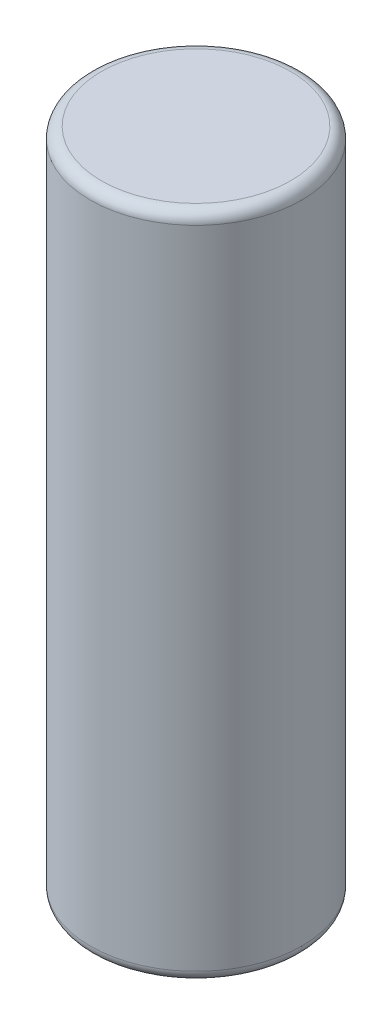
SolidWorks part; units mm, degrees
ref_plane "前视基准面" through (0, 0, 0) normal (0, 0, 1) x (1, 0, 0)
ref_plane "上视基准面" through (0, 0, 0) normal (0, 1, 0) x (1, 0, 0)
ref_plane "右视基准面" through (0, 0, 0) normal (1, 0, 0) x (0, 0, -1)
other "Configuration Table"
sketch "草图1" plane through (0, 0, 0) normal (0, 1, 0) x (1, 0, 0)
  circle A0 centre (0, 0) radius 9.5
  dimension "D1" = 19
extrude "凸台-拉伸1" add sketch "草图1" along normal blind 60
fillet "圆角1" radius 1 2 edges at (0, 0, 9.5) (0, 60, 9.5)
